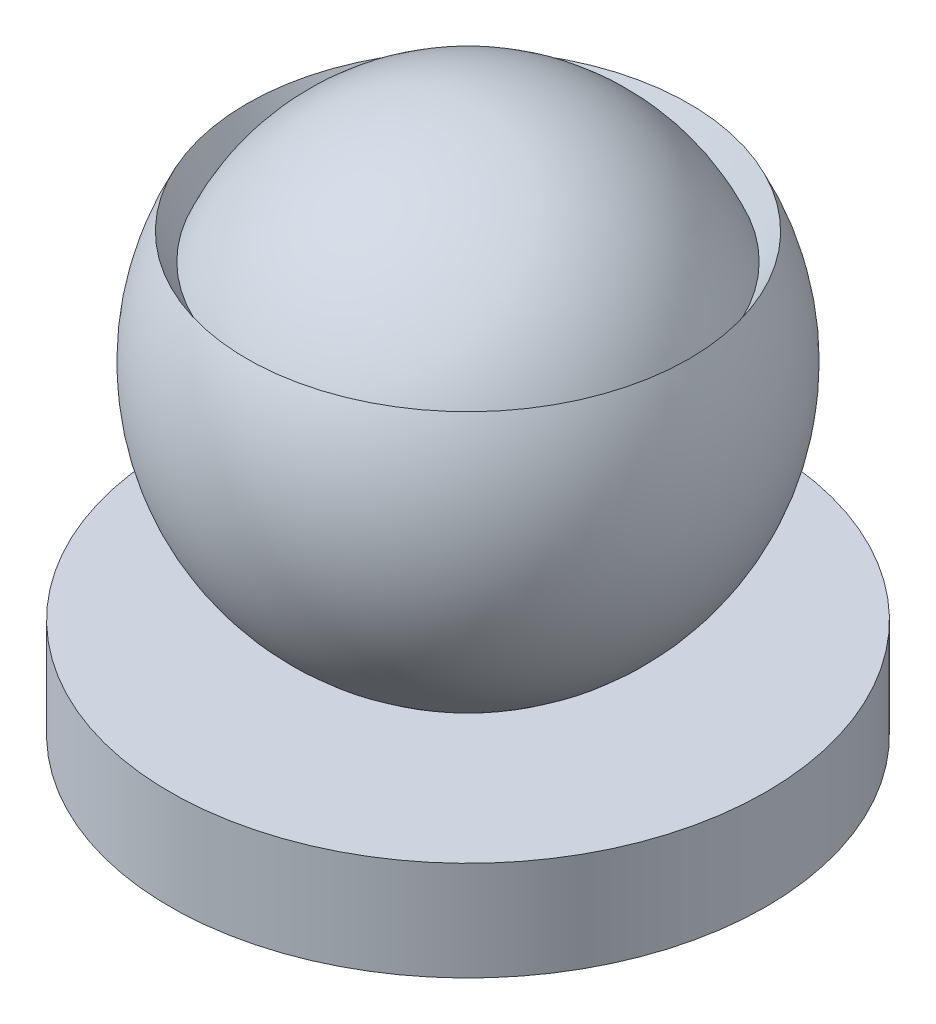
SolidWorks part; units mm, degrees
ref_plane "Front Plane" through (0, 0, 0) normal (0, 0, 1) x (1, 0, 0)
ref_plane "Top Plane" through (0, 0, 0) normal (0, 1, 0) x (1, 0, 0)
ref_plane "Right Plane" through (0, 0, 0) normal (1, 0, 0) x (0, 0, -1)
sketch "Sketch1" plane through (0, 0, 0) normal (0, 0, 1) x (1, 0, 0)
  line L0 (0, -13) -> (12, -13)
  line L1 (12, -13) -> (12, -9)
  line L2 (12, -9) -> (4.3589, -9)
  line L3 (0, 9) -> (0, -13)
  line L4 (8.2916, 3.5) -> (8.9016, 4.5566)
  line L5 (8.2916, 3.5) -> (10.2916, 3.5) construction
  arc A0 (8.2916, 3.5) -> (0, 9) centre (0, 0) ccw
  arc A1 (4.3589, -9) -> (8.9016, 4.5566) centre (0, 0) ccw
  dimension "D1" = 18
  dimension "D3" = 20
  dimension "D2" = 4
  dimension "D4" = 12
  dimension "D5" = 60
  dimension "D6" = 2
  dimension "D7" = 3.5
revolve "Revolve1" add sketch "Sketch1" angle 360 about L3
